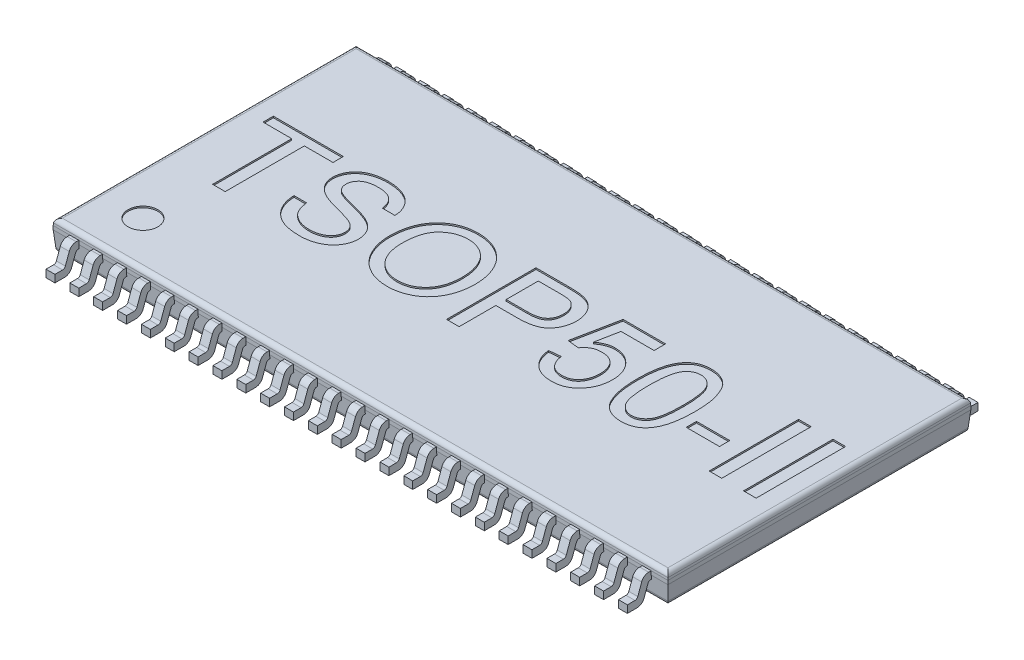
SolidWorks part; units mm, degrees
ref_plane "Спереди" through (0, 0, 0) normal (0, 0, 1) x (1, 0, 0)
ref_plane "Сверху" through (0, 0, 0) normal (0, 1, 0) x (1, 0, 0)
ref_plane "Справа" through (0, 0, 0) normal (1, 0, 0) x (0, 0, -1)
sketch "Sketch1" plane through (0, 0, 0) normal (0, 1, 0) x (1, 0, 0)
  line L1 (-10.31, -5.08) -> (10.31, -5.08)
  line L2 (-10.31, -5.08) -> (-10.31, 5.08)
  line L3 (-10.31, 5.08) -> (10.31, 5.08)
  line L4 (10.31, -5.08) -> (10.31, 5.08)
  line L5 (-10.31, -5.08) -> (10.31, 5.08) construction
  line L6 (-10.31, 5.08) -> (10.31, -5.08) construction
  point P0 (0, 0)
  dimension "D1" = 20.62
  dimension "D2" = 10.16
extrude "Boss-Extrude1" add sketch "Sketch1" against normal blind 0.665 draft 5 from offset 0.715
sketch "Sketch2" plane through (0, 0.715, 0) normal (0, 1, 0) x (1, 0, 0)
  line L4 (10.31, -5.08) -> (10.31, 5.08)
  line L5 (10.31, 5.08) -> (-10.31, 5.08)
  line L6 (-10.31, 5.08) -> (-10.31, -5.08)
  line L7 (-10.31, -5.08) -> (10.31, -5.08)
  line L8 (10.31, -5.08) -> (10.31, 5.08)
  line L9 (10.31, 5.08) -> (-10.31, 5.08)
  line L10 (-10.31, 5.08) -> (-10.31, -5.08)
  line L11 (-10.31, -5.08) -> (10.31, -5.08)
  dimension "D1" = 0
extrude "Boss-Extrude2" add sketch "Sketch2" along normal blind 0.125
sketch "Sketch3" plane through (0, 0.84, 0) normal (0, 1, 0) x (1, 0, 0)
  line L4 (-10.31, -5.08) -> (10.31, -5.08)
  line L5 (10.31, -5.08) -> (10.31, 5.08)
  line L6 (10.31, 5.08) -> (-10.31, 5.08)
  line L7 (-10.31, 5.08) -> (-10.31, -5.08)
  line L8 (-10.31, -5.08) -> (10.31, -5.08)
  line L9 (10.31, -5.08) -> (10.31, 5.08)
  line L10 (10.31, 5.08) -> (-10.31, 5.08)
  line L11 (-10.31, 5.08) -> (-10.31, -5.08)
  dimension "D1" = 0
extrude "Boss-Extrude3" add sketch "Sketch3" along normal blind 0.21 draft 5
fillet "Fillet1" radius 0.15 8 edges at (0, 0.05, -5.0218) (-10.2518, 0.05, 0) (0, 0.05, 5.0218) (10.2518, 0.05, 0) (0, 1.05, -5.0616) (10.2916, 1.05, 0) (0, 1.05, 5.0616) (-10.2916, 1.05, 0)
sketch "Sketch4" plane through (0, 0, 0) normal (1, 0, 0) x (0, 0, -1)
  line L1 (-5.88, 0.25) -> (-5.88, 0)
  line L2 (0, 0) -> (0, 1.3235) construction
  line L3 (-5.88, 0) -> (-5.5551, 0)
  line L5 (-5.3201, 0.1645) -> (-5.1892, 0.5242)
  line L7 (-5, 0.59) -> (-5, 0.84)
  line L8 (-5.0952, 0.59) -> (-5, 0.59)
  line L9 (-5.88, 0.25) -> (-5.6251, 0.25)
  line L10 (-5.5311, 0.3158) -> (-5.4002, 0.6755)
  line L11 (-5.1653, 0.84) -> (-5, 0.84)
  arc A0 (-5.4002, 0.6755) -> (-5.1653, 0.84) centre (-5.1653, 0.59) cw
  arc A1 (-5.5551, 0) -> (-5.3201, 0.1645) centre (-5.5551, 0.25) ccw
  arc A2 (-5.6251, 0.25) -> (-5.5311, 0.3158) centre (-5.6251, 0.35) ccw
  arc A3 (-5.1892, 0.5242) -> (-5.0952, 0.59) centre (-5.0952, 0.49) cw
  point P6 (-5, 1.3235)
  point P16 (-5.38, 0)
  dimension "D1" = 0.25
  dimension "D2" = 0.1
ref_plane "Plane1" through (-9.6, 0, 0) normal (1, 0, 0) x (0, 0, -1)
sketch "Sketch6" plane through (0, 0, 0) normal (0, 1, 0) x (1, 0, 0)
  line L0 (0, 0) -> (5.3717, 0) construction
sketch "Sketch5" plane through (-9.6, 0, 0) normal (1, 0, 0) x (0, 0, -1)
  line L0 (0, 0) -> (0, 2.6562) construction
  line L1 (5.0952, 0.59) -> (5, 0.59)
  line L2 (5, 0.59) -> (5, 0.84)
  line L3 (5, 0.84) -> (5.1653, 0.84)
  line L4 (5.4002, 0.6755) -> (5.5311, 0.3158)
  line L5 (5.6251, 0.25) -> (5.88, 0.25)
  line L6 (5.88, 0.25) -> (5.88, 0)
  line L7 (5.88, 0) -> (5.5551, 0)
  line L8 (-5.3201, 0.1645) -> (-5.1892, 0.5242)
  line L9 (-5.88, 0) -> (-5.5551, 0)
  line L10 (-5.88, 0.25) -> (-5.88, 0)
  line L11 (-5.6251, 0.25) -> (-5.88, 0.25)
  line L12 (-5.4002, 0.6755) -> (-5.5311, 0.3158)
  line L13 (-5, 0.84) -> (-5.1653, 0.84)
  line L14 (-5, 0.59) -> (-5, 0.84)
  line L15 (-5.0952, 0.59) -> (-5, 0.59)
  line L16 (-5.3201, 0.1645) -> (-5.1892, 0.5242)
  line L17 (-5.88, 0) -> (-5.5551, 0)
  line L18 (-5.88, 0.25) -> (-5.88, 0)
  line L19 (-5.6251, 0.25) -> (-5.88, 0.25)
  line L20 (-5.4002, 0.6755) -> (-5.5311, 0.3158)
  line L21 (-5, 0.84) -> (-5.1653, 0.84)
  line L22 (-5, 0.59) -> (-5, 0.84)
  line L23 (-5.0952, 0.59) -> (-5, 0.59)
  line L24 (5.3201, 0.1645) -> (5.1892, 0.5242)
  arc A0 (5.0952, 0.59) -> (5.1892, 0.5242) centre (5.0952, 0.49) cw
  arc A1 (5.1653, 0.84) -> (5.4002, 0.6755) centre (5.1653, 0.59) cw
  arc A2 (5.6251, 0.25) -> (5.5311, 0.3158) centre (5.6251, 0.35) cw
  arc A3 (5.5551, 0) -> (5.3201, 0.1645) centre (5.5551, 0.25) cw
  arc A4 (-5.5551, 0) -> (-5.3201, 0.1645) centre (-5.5551, 0.25) ccw
  arc A5 (-5.6251, 0.25) -> (-5.5311, 0.3158) centre (-5.6251, 0.35) ccw
  arc A6 (-5.1653, 0.84) -> (-5.4002, 0.6755) centre (-5.1653, 0.59) ccw
  arc A7 (-5.0952, 0.59) -> (-5.1892, 0.5242) centre (-5.0952, 0.49) ccw
  arc A8 (-5.5551, 0) -> (-5.3201, 0.1645) centre (-5.5551, 0.25) ccw
  arc A9 (-5.6251, 0.25) -> (-5.5311, 0.3158) centre (-5.6251, 0.35) ccw
  arc A10 (-5.1653, 0.84) -> (-5.4002, 0.6755) centre (-5.1653, 0.59) ccw
  arc A11 (-5.0952, 0.59) -> (-5.1892, 0.5242) centre (-5.0952, 0.49) ccw
  dimension "D1" = 0
extrude "Boss-Extrude4" add sketch "Sketch5" along normal mid plane 0.3 separate body
pattern_linear "LPattern1" count 25 spacing 0.8 along (1, 0, 0) of "Boss-Extrude4"
sketch "Sketch7" plane through (0, 1.05, 0) normal (0, 1, 0) x (1, 0, 0)
  line L0 (-10.3036, -5.0736) -> (-10.3036, 5.0736) construction
  line L1 (10.3036, -5.0736) -> (-10.3036, -5.0736) construction
  circle A0 centre (-8.8036, -3.5736) radius 0.5
  text T0 "TSOP50-II" font "Arial" height 3
  dimension "D1" = 1.5
  dimension "D2" = 1.5
extrude "Cut-Extrude1" cut sketch "Sketch7" against normal blind 0.05
